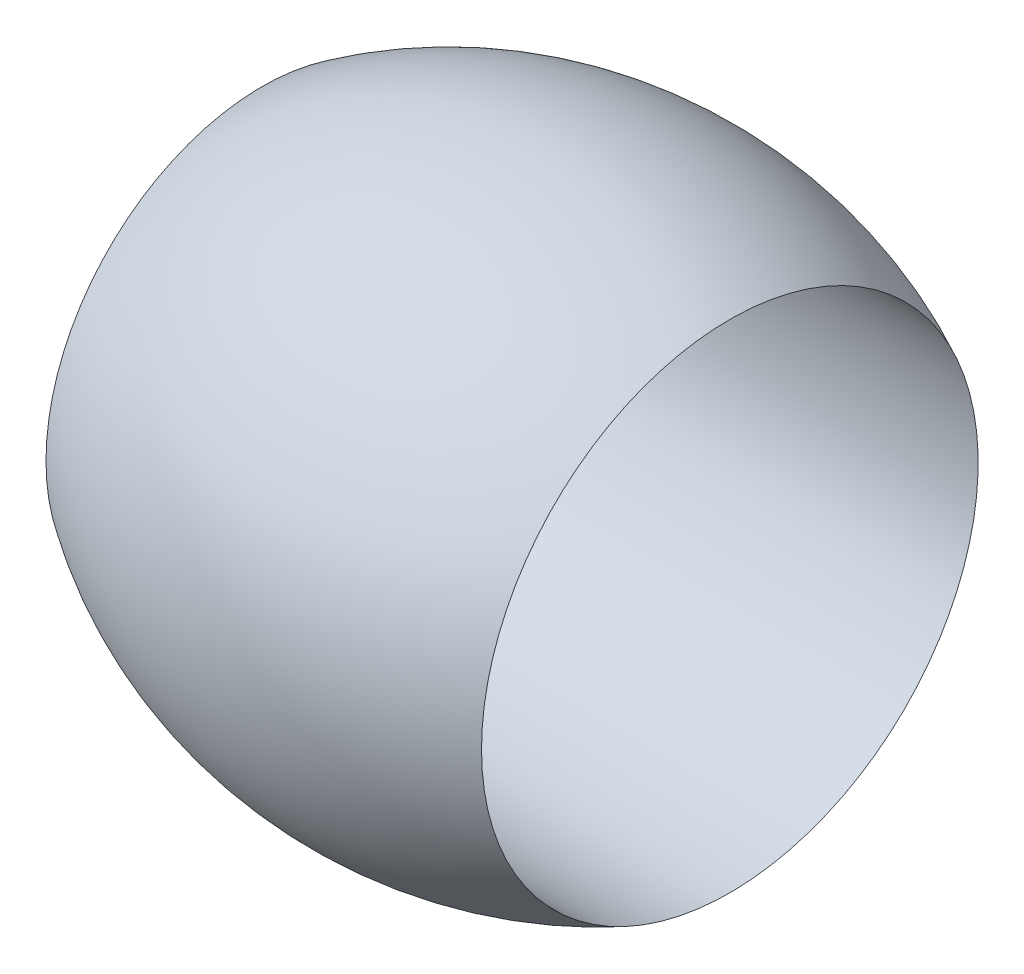
SolidWorks part; units mm, degrees
ref_plane "Front Plane" through (0, 0, 0) normal (0, 0, 1) x (1, 0, 0)
ref_plane "Top Plane" through (0, 0, 0) normal (0, 1, 0) x (1, 0, 0)
ref_plane "Right Plane" through (0, 0, 0) normal (1, 0, 0) x (0, 0, -1)
sketch "Sketch1" plane through (0, 0, 0) normal (0, 0, 1) x (1, 0, 0)
  line L0 (0, -55) -> (0, 55) construction
  line L1 (55, 0) -> (-55, 0) construction
  line L3 (-38.608, 0) -> (-38.608, 22.86)
  line L4 (-38.608, 22.86) -> (-41.91, 22.86)
  line L5 (-41.91, 31.75) -> (-41.91, 36.0045)
  line L7 (-42.418, 0) -> (-38.608, 0)
  line L9 (-30.226, 36.0045) -> (-41.91, 36.0045)
  line L10 (-45.72, 37.7954) -> (-45.72, 19.05)
  line L14 (-30.226, 43.4274) -> (36.0781, 43.4274)
  line L17 (-45.72, 19.05) -> (-42.418, 19.05)
  line L18 (-42.418, 19.05) -> (-42.418, 0)
  line L19 (-41.91, 31.75) -> (-42.21, 31.75)
  line L20 (-42.21, 31.75) -> (-42.21, 22.86)
  line L21 (-42.21, 22.86) -> (-41.91, 22.86)
  line L22 (-30.226, 36.0045) -> (-30.226, 43.4274)
  arc A1 (36.0781, 43.4274) -> (-45.72, 37.7954) centre (0, -29.4067) ccw
  dimension "D1" = 81.28
  dimension "D2" = 43.4274
  dimension "D3" = 45.72
  dimension "D4" = 22.86
  dimension "D5" = 7.112
  dimension "D6" = 11.684
  dimension "D7" = 29.4067
  dimension "D8" = 3.81
  dimension "D9" = 36.0045
  dimension "D12" = 3.81
  dimension "D13" = 3.81
  dimension "D14" = 0.3
  dimension "D15" = 8.89
revolve "Revolve1" add sketch "Sketch1" angle 360 about L7
fillet "Fillet1" radius 2.54 1 edges at (-30.226, 0, 43.4274)
